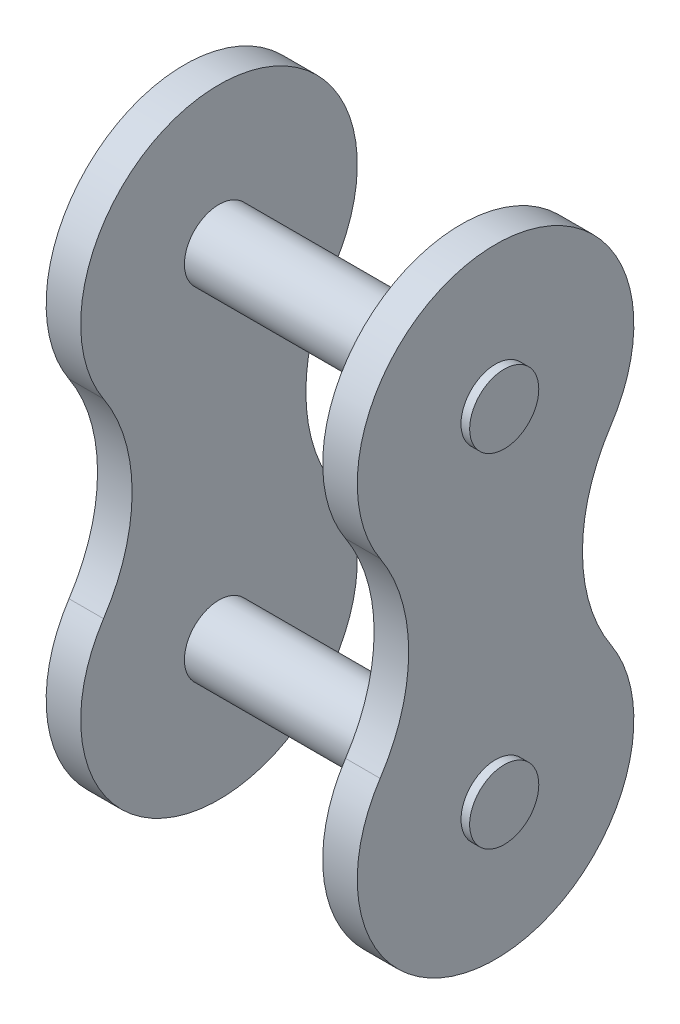
SolidWorks part; units mm, degrees
material "AISI 1045 Steel, cold drawn"
ref_plane "Front Plane" through (0, 0, 0) normal (1, 0, 0) x (0, 1, 0)
ref_plane "Top Plane" through (0, 0, 0) normal (0, 0, 1) x (0, 1, 0)
ref_plane "Right Plane" through (0, 0, 0) normal (0, 1, 0) x (-1, 0, 0)
sketch "Sketch1" plane through (0, 0, 0) normal (1, 0, 0) x (0, 1, 0)
  line L0 (0, 12.7808) -> (0, -15.8138) construction
  line L1 (-18.4439, 0) -> (19.2136, 0) construction
  arc A0 (-2.7528, 3.3392) -> (-2.7528, -3.3392) centre (-4.955, 0) ccw
  circle A1 centre (-4.955, 0) radius 1
  circle A2 centre (4.955, 0) radius 1
  arc A3 (2.7528, 3.3392) -> (2.7528, -3.3392) centre (4.955, 0) cw
  arc A4 (-2.7528, 3.3392) -> (2.7528, 3.3392) centre (0, 7.5132) ccw
  arc A5 (-2.7528, -3.3392) -> (2.7528, -3.3392) centre (0, -7.5132) cw
  dimension "D1" = 8
  dimension "D3" = 2
  dimension "D4" = 5
  dimension "D2" = 4.955
extrude "Boss-Extrude1" add sketch "Sketch1" along normal blind 1 from offset 3.5
mirror "Mirror2" about plane through (0, 0, 0) normal (1, 0, 0) of bodies 101
sketch "Sketch2" plane through (0, 0, 0) normal (1, 0, 0) x (0, 1, 0)
  circle A0 centre (-4.955, 0) radius 1 construction
  circle A1 centre (-4.955, 0) radius 1
  circle A2 centre (4.955, 0) radius 1 construction
  circle A3 centre (4.955, 0) radius 1
extrude "Boss-Extrude2" add sketch "Sketch2" along normal mid plane 9.5
